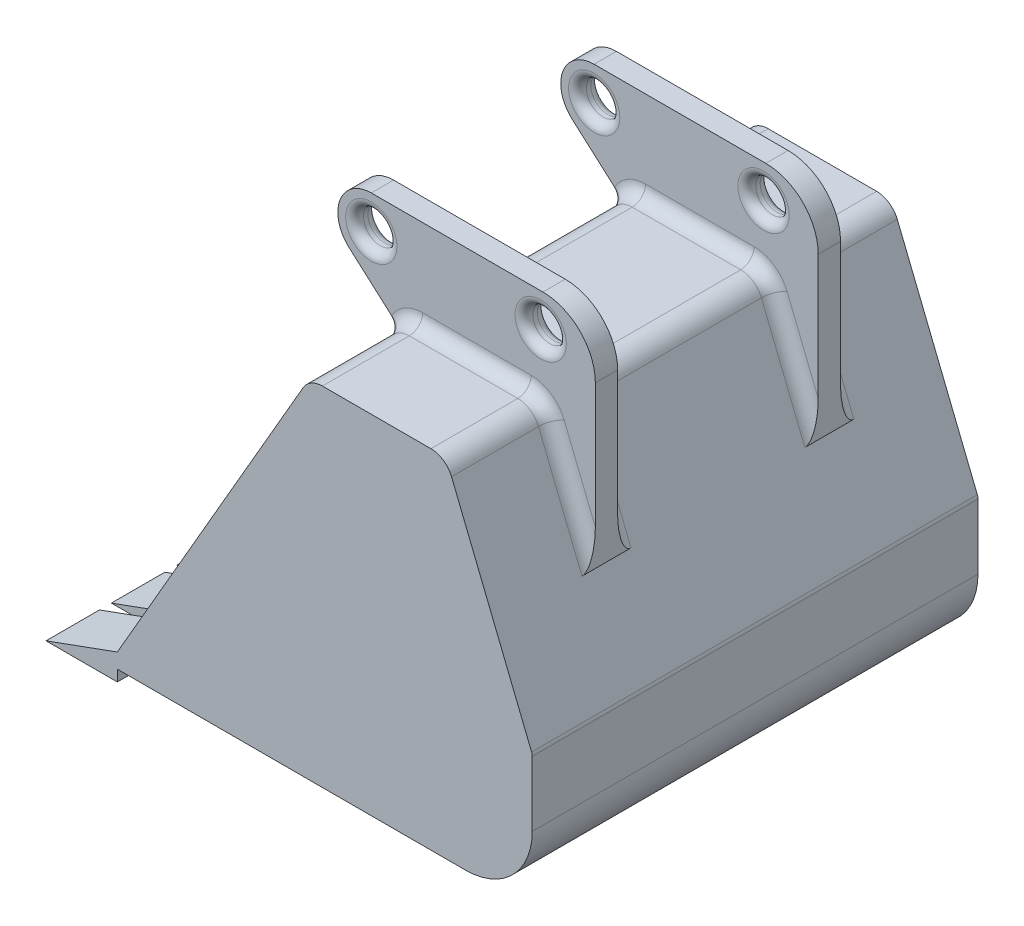
SolidWorks part; units mm, degrees
ref_plane "Front Plane" through (0, 0, 0) normal (0, 0, 1) x (1, 0, 0)
ref_plane "Top Plane" through (0, 0, 0) normal (0, 1, 0) x (1, 0, 0)
ref_plane "Right Plane" through (0, 0, 0) normal (1, 0, 0) x (0, 0, -1)
sketch "Sketch1" plane through (0, 0, 0) normal (0, 0, 1) x (1, 0, 0)
  line L0 (0, -150) -> (-800, -150)
  line L1 (150, 0) -> (150, 150)
  line L2 (150, 150) -> (-43.6668, 630)
  line L3 (-43.6668, 630) -> (-349.6668, 630)
  line L4 (-349.6668, 630) -> (-800, -150)
  arc A0 (0, -150) -> (150, 0) centre (0, 0) ccw
  dimension "D1" = 150
  dimension "D2" = 150
  dimension "D3" = 800
  dimension "D4" = 60
  dimension "D5" = 780
  dimension "D6" = 306
extrude "Boss-Extrude1" add sketch "Sketch1" along normal blind 1000
shell "Shell1" thickness 35
fillet "Fillet1" radius 20 1 edges at (150, 150, 500)
fillet "Fillet2" radius 50 1 edges at (-43.6668, 630, 500)
sketch "Sketch2" plane through (0, 0, 1000) normal (0, 0, 1) x (1, 0, 0)
  line L0 (-780.8116, -116.7648) -> (-780.8116, -175)
  line L1 (-349.6668, 630) -> (-800, -150) construction
  line L2 (-780.8116, -175) -> (-940.8116, -175)
  line L3 (-940.8116, -175) -> (-780.8116, -116.7648)
  line L4 (-800, -150) -> (0, -150) construction
  dimension "D1" = 160
  dimension "D2" = 25
  dimension "D3" = 160
extrude "Boss-Extrude2" add sketch "Sketch2" against normal blind 120
pattern_linear "LPattern1" count 7 spacing 146.6 along (0, 0, -1) of "Boss-Extrude2"
ref_plane "Plane1" through (0, 0, 250) normal (0, 0, 1) x (1, 0, 0)
ref_plane "Plane3" through (0, 0, 750) normal (0, 0, 1) x (1, 0, 0)
sketch "Sketch3" plane through (0, 0, 250) normal (0, 0, 1) x (1, 0, 0)
  line L1 (-349.6668, 630) -> (-780.8116, -116.7648) construction
  line L2 (-436.0753, 835) -> (-51.0753, 835)
  line L3 (66.5905, 717.3342) -> (66.5905, 356.7292)
  line L4 (-367.5933, 598.9503) -> (-485.8576, 703.9043)
  line L12 (-349.6668, 630) -> (-780.8116, -116.7648)
  line L13 (-780.8116, -116.7648) -> (-940.8116, -175)
  line L14 (-940.8116, -175) -> (-780.8116, -175)
  line L15 (-780.8116, -175) -> (-780.8116, -150)
  line L16 (-780.8116, -150) -> (0, -150)
  line L17 (150, 0) -> (150, 146.1173)
  line L18 (148.5472, 153.6006) -> (-31.0414, 598.7083)
  line L19 (-77.4095, 630) -> (-349.6668, 630)
  line L20 (-349.6668, 630) -> (-367.5933, 598.9503)
  line L26 (66.5905, 356.7292) -> (-31.0414, 598.7083)
  line L27 (-77.4095, 630) -> (-349.6668, 630)
  arc A1 (66.5905, 717.3342) -> (-51.0753, 835) centre (-51.0753, 717.3342) ccw
  arc A2 (-436.0753, 835) -> (-485.8576, 703.9043) centre (-436.0753, 760) ccw
  arc A5 (0, -150) -> (150, 0) centre (0, 0) ccw
  arc A6 (150, 146.1173) -> (148.5472, 153.6006) centre (130, 146.1173) ccw
  arc A7 (-31.0414, 598.7083) -> (-77.4095, 630) centre (-77.4095, 580) ccw
  arc A9 (150, 146.1173) -> (148.5472, 153.6006) centre (130, 146.1173) ccw
  arc A10 (-31.0414, 598.7083) -> (-77.4095, 630) centre (-77.4095, 580) ccw
  point P1 (0, 0)
  point P3 (-367.5933, 598.7083)
  dimension "D1" = 0
  dimension "D2" = 385
  dimension "D3" = 75
  dimension "D4" = 205
  dimension "D5" = 144
extrude "Boss-Extrude3" add sketch "Sketch3" along normal mid plane 50 contours L2 A1 L3 L26 A10 L27 L20 L4 A2
ref_plane "Plane4" through (0, 0, 500) normal (0, 0, 1) x (1, 0, 0)
mirror "Mirror1" about plane through (0, 0, 500) normal (0, 0, 1) of "Boss-Extrude3"
sketch "Sketch4" plane through (0, 0, 775) normal (0, 0, 1) x (1, 0, 0)
  circle A0 centre (-436.0753, 760) radius 37.5
  circle A1 centre (-56.0753, 760) radius 37.5
extrude "Cut-Extrude1" cut sketch "Sketch4" against normal through all
fillet "Fillet3" radius 50 3 edges at (-349.6668, 630, 112.5) (-349.6668, 630, 887.5) (-349.6668, 630, 500)
fillet "Fillet4" radius 20 8 edges at (-473.5753, 760, 725) (-398.5753, 760, 775) (-18.5753, 760, 775) (-93.5753, 760, 725) (-18.5753, 760, 225) (-398.5753, 760, 225) (-398.5753, 760, 275) (-18.5753, 760, 275)
fillet "Fillet5" radius 30 20 edges at (17.7745, 477.7187, 225) (-49.44, 621.4452, 225) (-365.8469, 601.9751, 225) (-345.7993, 623.3013, 225) (17.7745, 477.7187, 725) (-49.44, 621.4452, 725) (-365.8469, 601.9751, 725) (-345.7993, 623.3013, 725) (17.7745, 477.7187, 275) (-49.44, 621.4452, 275) (-365.8469, 601.9751, 275) (-345.7993, 623.3013, 275) (17.7745, 477.7187, 775) (-49.44, 621.4452, 775) (-365.8469, 601.9751, 775) (-345.7993, 623.3013, 775) (-199.1044, 630, 225) (-199.1044, 630, 725) (-199.1044, 630, 275) (-199.1044, 630, 775)
